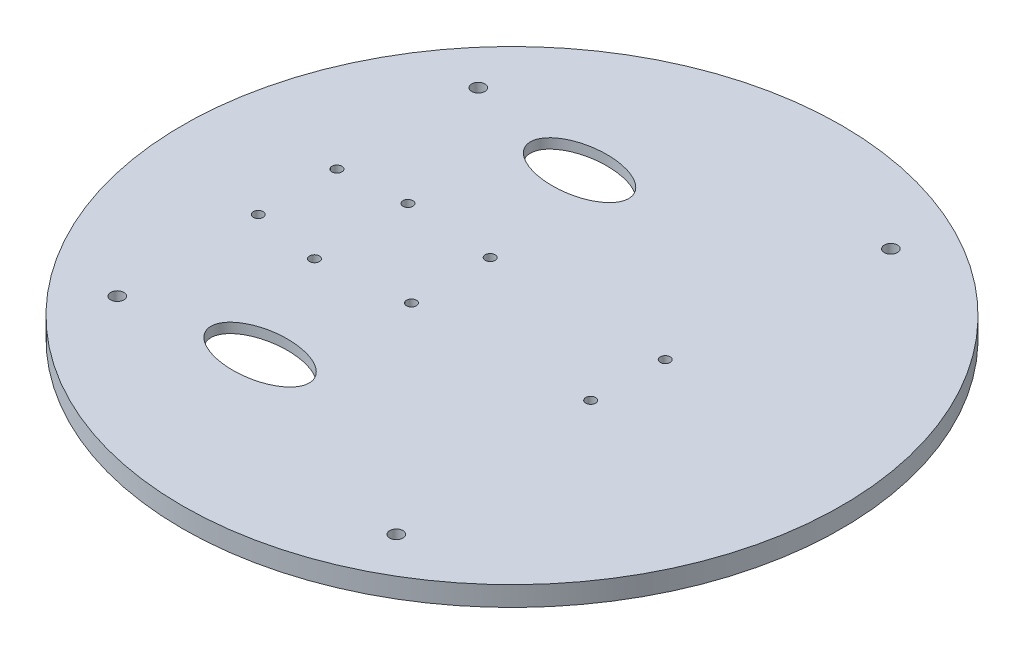
SolidWorks part; units mm, degrees
ref_plane "Спереди" through (0, 0, 0) normal (0, 0, 1) x (1, 0, 0)
ref_plane "Сверху" through (0, 0, 0) normal (0, 1, 0) x (1, 0, 0)
ref_plane "Справа" through (0, 0, 0) normal (1, 0, 0) x (0, 0, -1)
other "Configuration Table"
sketch "Эскиз1" plane through (0, 0, 0) normal (0, 1, 0) x (1, 0, 0)
  circle A0 centre (0, 0) radius 100
extrude "Бобышка-Вытянуть1" add sketch "Эскиз1" along normal blind 3
sketch "Эскиз5" plane through (0, 3, 0) normal (0, 1, 0) x (1, 0, 0)
  circle A1 centre (39.9369, -75.0336) radius 2
  circle A2 centre (39.9369, 75.0336) radius 2
  circle A4 centre (-65, 54.7723) radius 2
  circle A5 centre (-65, -54.7723) radius 2
extrude "Вырез-Вытянуть3" cut sketch "Эскиз5" against normal blind 10
sketch "Эскиз6" plane through (0, 3, 0) normal (0, 1, 0) x (1, 0, 0)
  line L3 (0, 0) -> (-36.9663, 0) construction
  line L4 (34.8287, 11.6657) -> (34.2098, -10.3403) construction
  line L5 (34.2098, -10.3403) -> (-45.2499, 13.6773) construction
  line L6 (-44.8932, -15.0367) -> (34.8287, 11.6657) construction
  circle A1 centre (-65.0644, 11.94) radius 1.5
  circle A2 centre (-18.5644, 11.94) radius 1.5
  circle A3 centre (-18.5644, -11.94) radius 1.5
  circle A4 centre (-65.0644, -11.94) radius 1.5
  circle A17 centre (34.2098, -10.3403) radius 1.5
  circle A18 centre (34.8287, 11.6657) radius 1.5
  circle A19 centre (-45.2499, 13.6773) radius 1.5
  circle A20 centre (-44.8932, -15.0367) radius 1.5
extrude "Вырез-Вытянуть4" cut sketch "Эскиз6" against normal blind 10
sketch "Эскиз7" plane through (0, 3, 0) normal (0, 1, 0) x (1, 0, 0)
  line L0 (100, 0) -> (-100, 0) construction
  circle A0 centre (0, 0) radius 100 construction
  ellipse E0 centre (-27.965, 48.4727) end of major axis (-13.0504, 48.4727) minor radius 8.2563
  ellipse E1 centre (-27.965, -48.4727) end of major axis (-13.0504, -48.4727) minor radius 8.2563
  point P13 (0, 0)
  point P20 (-27.965, -48.4727)
extrude "Вырез-Вытянуть5" cut sketch "Эскиз7" against normal blind 10
sketch "Эскиз9" plane through (0, 0, 0) normal (0, -1, 0) x (1, 0, 0)
  circle A0 centre (0, 0) radius 100
  circle A1 centre (0, 0) radius 97
extrude "Бобышка-Вытянуть3" add sketch "Эскиз9" along normal blind 3
